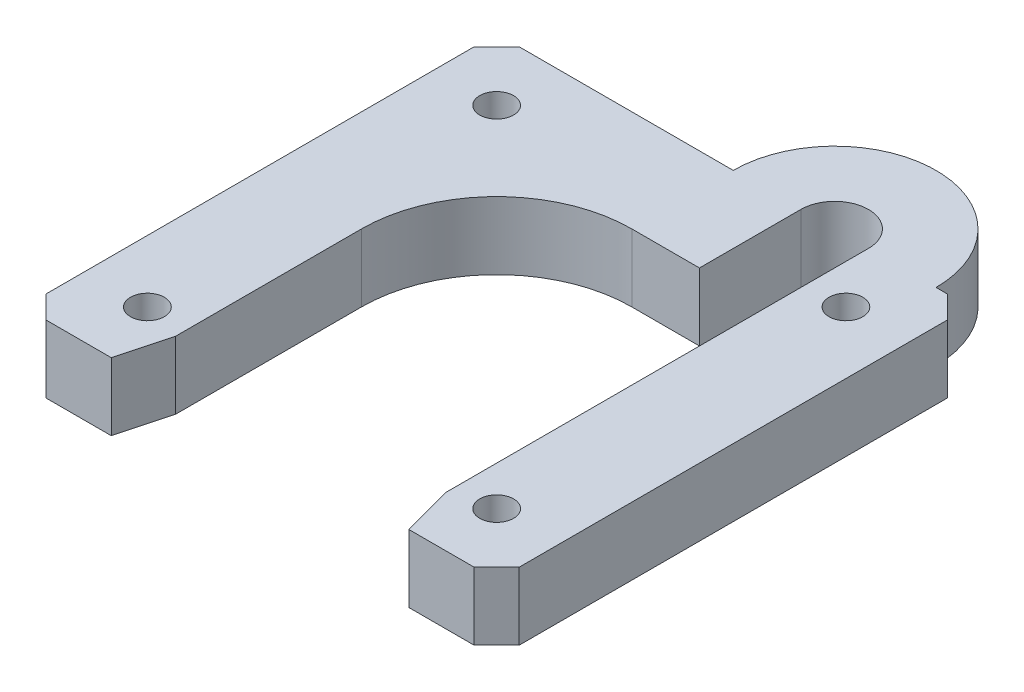
SolidWorks part; units mm, degrees
ref_plane "Front Plane" through (0, 0, 0) normal (0, 0, 1) x (1, 0, 0)
ref_plane "Top Plane" through (0, 0, 0) normal (0, 1, 0) x (1, 0, 0)
ref_plane "Right Plane" through (0, 0, 0) normal (1, 0, 0) x (0, 0, -1)
sketch "Sketch1" plane through (0, 0, 0) normal (0, 1, 0) x (1, 0, 0)
  line L1 (-21, -21) -> (21, -21)
  line L2 (-21, -21) -> (-21, 21)
  line L3 (-21, 21) -> (21, 21)
  line L4 (21, -21) -> (21, 21)
  line L5 (-21, -21) -> (21, 21) construction
  line L6 (-21, 21) -> (21, -21) construction
  line L7 (-15.5, 15.5) -> (15.5, 15.5) construction
  line L8 (-15.5, 15.5) -> (-15.5, -15.5) construction
  line L9 (-15.5, -15.5) -> (15.5, -15.5) construction
  line L10 (15.5, 15.5) -> (15.5, -15.5) construction
  circle A0 centre (0, 0) radius 12
  circle A1 centre (-15.5, 15.5) radius 1.5
  circle A2 centre (15.5, 15.5) radius 1.5
  circle A3 centre (15.5, -15.5) radius 1.5
  circle A4 centre (-15.5, -15.5) radius 1.5
  point P0 (0, 0)
  dimension "D2" = 24
  dimension "D3" = 3
  dimension "D1" = 42
  dimension "D4" = 31
extrude "Boss-Extrude1" add sketch "Sketch1" along normal blind 6
chamfer "Chamfer1" distance 2 angle 45 4 edges at (-21, 3, -21) (21, 3, -21) (21, 3, 21) (-21, 3, 21)
sketch "Sketch2" plane through (0, 6, 0) normal (0, 1, 0) x (1, 0, 0)
  line L0 (-12, 0) -> (-12, -21)
  line L1 (-19, -21) -> (19, -21) construction
  line L2 (-12, -21) -> (12, -21)
  line L3 (12, -21) -> (12, 0)
  line L4 (12, 0) -> (-12, 0)
  circle A0 centre (0, 0) radius 12 construction
extrude "Cut-Extrude1" cut sketch "Sketch2" against normal through all
chamfer "Chamfer2" distance 4.5 angle 15 2 edges at (12, 3, 21) (-12, 3, 21)
sketch "Sketch3" plane through (0, 6, 0) normal (0, 1, 0) x (1, 0, 0)
  line L0 (12, 0) -> (12, 21) construction
  line L1 (19, 21) -> (-19, 21) construction
  line L2 (6, 21) -> (6, 12) construction
  line L3 (0, 21) -> (0, 12) construction
  line L4 (0, 12) -> (6, 12) construction
  line L5 (0, 21) -> (6, 21)
  line L6 (18, 21) -> (12, 21)
  arc A0 (12, 21) -> (6, 21) centre (9, 21) ccw
  arc A1 (0, 21) -> (18, 21) centre (9, 21) cw
  arc A3 (12, 0) -> (-12, 0) centre (0, 0) ccw construction
  dimension "D1" = 6
  dimension "D2" = 3
extrude "Boss-Extrude2" add sketch "Sketch3" against normal up to surface (6 mm away) up to face at (0, 0, 4.5)
sketch "Sketch4" plane through (0, 6, 6) normal (0, 1, 0) x (1, 0, 0)
  line L0 (12, 6) -> (12, 27)
  line L2 (6, 27) -> (6, 18)
  line L3 (-3.575, 6) -> (3.575, 6) construction
  line L4 (0, 18) -> (6, 18)
  line L5 (0, 18) -> (0, 6)
  line L6 (0, 6) -> (12, 6)
  line L7 (0, 2.425) -> (0, 9.575) construction
  arc A0 (12, 27) -> (6, 27) centre (9, 27) ccw
  arc A3 (12, 27) -> (6, 27) centre (9, 27) ccw construction
  arc A4 (12, 6) -> (-12, 6) centre (0, 6) ccw construction
  dimension "D2" = 3
extrude "Cut-Extrude2" cut sketch "Sketch4" against normal through all
equation "\"M3_d\"= \"M3_d_laser@troublemaker.Assembly\""
equation "\"housing_t\"= \"housing_t_glob@troublemaker.Assembly\""
equation "\"D3@Sketch1\"=\"M3_d\""
equation "\"D1@Boss-Extrude1\"=\"housing_t\""
